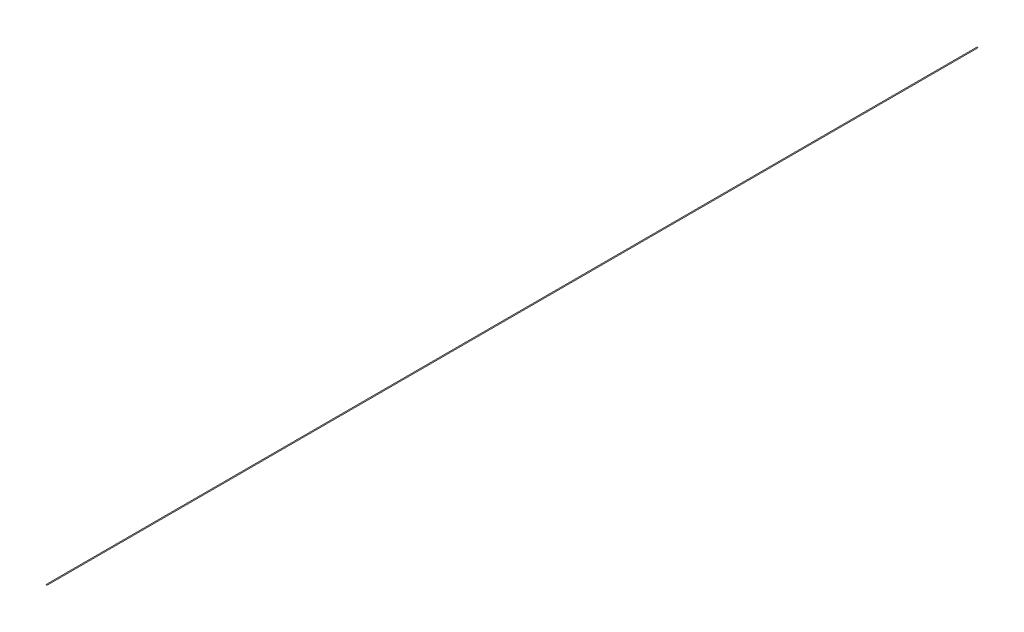
SolidWorks part; units mm, degrees
ref_plane "前视基准面" through (0, 0, 0) normal (0, 0, 1) x (1, 0, 0)
ref_plane "上视基准面" through (0, 0, 0) normal (0, 1, 0) x (1, 0, 0)
ref_plane "右视基准面" through (0, 0, 0) normal (1, 0, 0) x (0, 0, -1)
sketch "草图1" plane through (0, 0, 0) normal (0, 0, 1) x (1, 0, 0)
  line L0 (0, 34.641) -> (-30, 0)
  line L1 (-30, 0) -> (30, 0)
  line L2 (30, 0) -> (0, 34.641)
extrude "凸台-拉伸1" add sketch "草图1" along normal blind 50000
